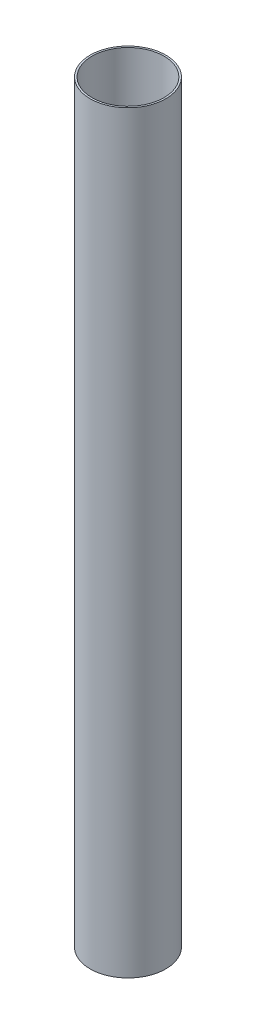
SolidWorks part; units mm, degrees
ref_plane "Front Plane" through (0, 0, 0) normal (0, 0, 1) x (1, 0, 0)
ref_plane "Top Plane" through (0, 0, 0) normal (0, 1, 0) x (1, 0, 0)
ref_plane "Right Plane" through (0, 0, 0) normal (1, 0, 0) x (0, 0, -1)
sketch "Sketch1" plane through (0, 0, 0) normal (0, 1, 0) x (1, 0, 0)
  circle A0 centre (0, 0) radius 25.1
  circle A1 centre (0, 0) radius 23.9
  dimension "D1" = 50.2
  dimension "D2" = 47.8
extrude "Boss-Extrude1" add sketch "Sketch1" along normal blind 500
equation "\"tmp\"=82.4866"
equation "\"D1@Sketch1\"=\"TubeOutsideDiameter\""
equation "\"TubeOutsideDiameter\"= 50.2"
equation "\"TubeInnerDiameter\"= 47.8"
equation "\"ReleaseMechanisumHeight\"=100"
equation "\"WireDiameter\"=1.65"
equation "\"servoHoleDiameter\"= 2.8"
equation "\"CordDiameter\"= 5"
equation "\"MountingBoldDiameter\"=2.8"
equation "\"TubeMountingBoltDiameter\"= 5"
equation "\"CardTubeOutsideDiameter\"= 54.2"
equation "\"CardTubeInsideDiameter\"= 50.4"
equation "\"D2@Sketch1\"=\"TubeInnerDiameter\""
